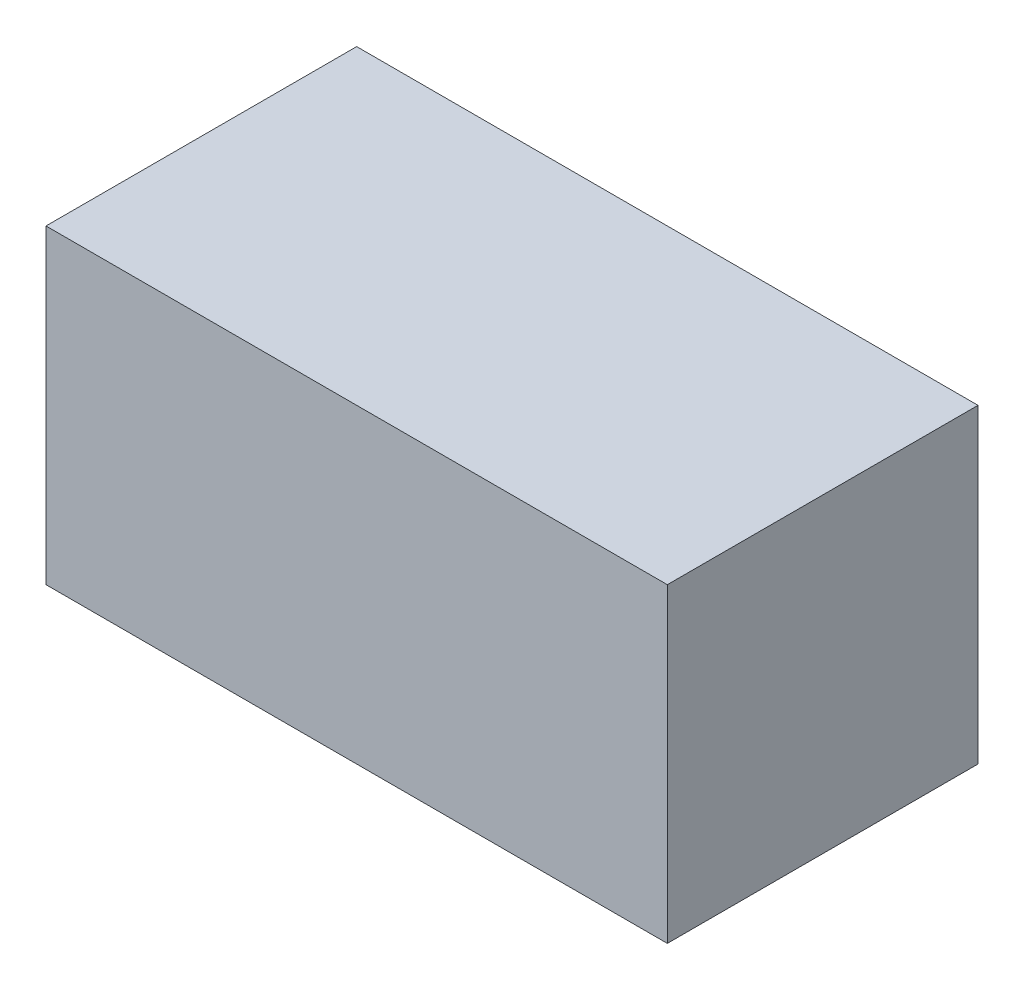
SolidWorks part; units mm, degrees
ref_plane "Front Plane" through (0, 0, 0) normal (0, 0, 1) x (1, 0, 0)
ref_plane "Top Plane" through (0, 0, 0) normal (0, 1, 0) x (1, 0, 0)
ref_plane "Right Plane" through (0, 0, 0) normal (1, 0, 0) x (0, 0, -1)
sketch "Sketch1" plane through (0, 0, 0) normal (0, 1, 0) x (1, 0, 0)
  line L0 (-6.35, 0) -> (6.35, 0) construction
  line L1 (-6.35, 3.175) -> (6.35, 3.175)
  line L2 (-6.35, 3.175) -> (-6.35, -3.175)
  line L3 (-6.35, -3.175) -> (6.35, -3.175)
  line L4 (6.35, 3.175) -> (6.35, -3.175)
  dimension "Square Size" = 6.35
  dimension "Length" = 12.7
extrude "Extrude1" add sketch "Sketch1" against normal blind 6.35
sketch "Sketch2" plane through (44.45, 6.35, 3.175) normal (0, 0, -1) x (-1, 0, 0)
  line L0 (41.275, -9.525) -> (47.625, -9.525) construction
  line L1 (41.275, -6.35) -> (47.625, -6.35)
  line L2 (41.275, -12.7) -> (47.625, -12.7)
  line L5 (50.8, -9.525) -> (47.625, -9.525) construction
  line L6 (41.275, -9.525) -> (38.1, -9.525) construction
  line L7 (38.1, -12.7) -> (38.1, -6.35) construction
  line L8 (50.8, -12.7) -> (50.8, -6.35) construction
  line L9 (38.1, -6.35) -> (50.8, -6.35) construction
  arc A0 (41.275, -6.35) -> (41.275, -12.7) centre (41.275, -9.525) ccw
  arc A1 (47.625, -12.7) -> (47.625, -6.35) centre (47.625, -9.525) ccw
  point P2 (44.45, -9.525)
extrude "Extrude2" [suppressed] cut sketch "Sketch2" along normal through all flip side to cut
sketch "Sketch3" plane through (0, 0, 0) normal (0, 1, 0) x (1, 0, 0)
  line L0 (0, -3.175) -> (0, 3.175) construction
  line L1 (-6.35, -3.175) -> (6.35, -3.175) construction
  line L2 (6.35, 3.175) -> (-6.35, 3.175) construction
  dimension "D1" = 6.35
